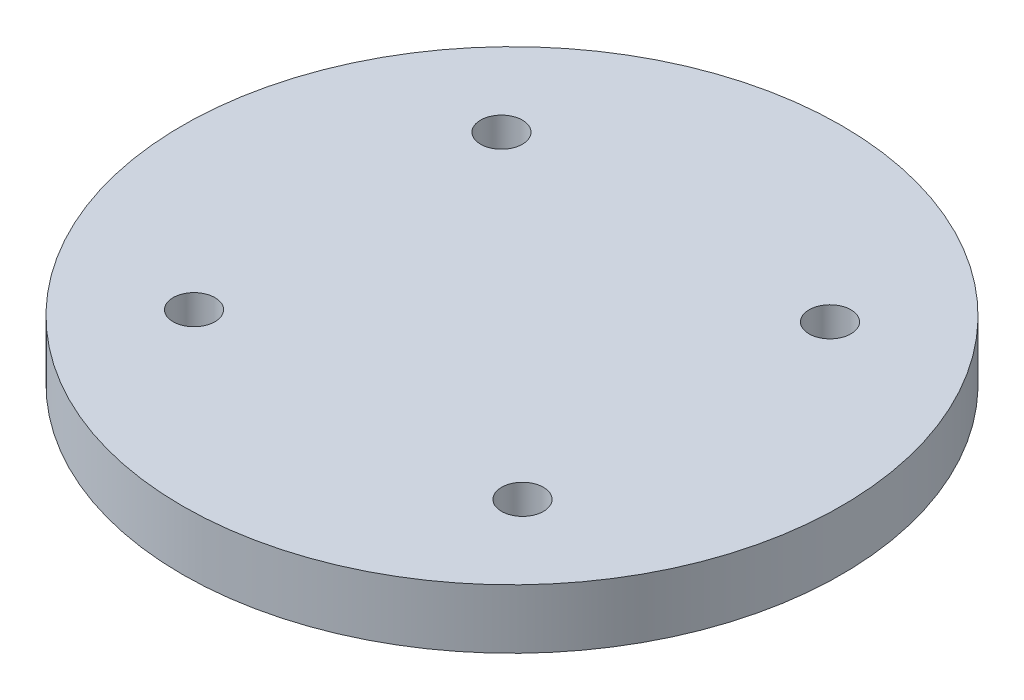
SolidWorks part; units mm, degrees
ref_plane "Front Plane" through (0, 0, 0) normal (0, 0, 1) x (1, 0, 0)
ref_plane "Top Plane" through (0, 0, 0) normal (0, 1, 0) x (1, 0, 0)
ref_plane "Right Plane" through (0, 0, 0) normal (1, 0, 0) x (0, 0, -1)
sketch "Sketch1" plane through (0, 0, 0) normal (0, 1, 0) x (1, 0, 0)
  line L0 (-59, 55.5) -> (-59, -55.5)
  line L1 (-50, 46.5) -> (50, 46.5)
  line L2 (-50, 46.5) -> (-50, -46.5)
  line L3 (-50, -46.5) -> (50, -46.5)
  line L4 (50, 46.5) -> (50, -46.5)
  line L5 (-50, 46.5) -> (50, -46.5) construction
  line L6 (-50, -46.5) -> (50, 46.5) construction
  line L7 (-59, -55.5) -> (59, -55.5)
  line L8 (59, 55.5) -> (59, -55.5)
  line L9 (-59, 55.5) -> (59, 55.5)
  circle A0 centre (0, 0) radius 81.0015
  circle A1 centre (0, 0) radius 50
  point P0 (0, 0)
  dimension "D4" = 100
  dimension "D1" = 100
  dimension "D2" = 93
  dimension "D3" = 9
extrude "Boss-Extrude1" add sketch "Sketch1" along normal blind 9 contours A1
sketch "Sketch2" plane through (0, 9, 0) normal (0, 1, 0) x (1, 0, 0)
  line L0 (0, 23.325) -> (0, -23.325) construction
  line L1 (-24.92, 23.325) -> (24.92, 23.325)
  line L2 (-24.92, 23.325) -> (-24.92, -23.325)
  line L3 (-24.92, -23.325) -> (24.92, -23.325)
  line L4 (24.92, 23.325) -> (24.92, -23.325)
  line L5 (-24.92, 23.325) -> (24.92, -23.325) construction
  line L6 (-24.92, -23.325) -> (24.92, 23.325) construction
  line L7 (-24.92, 0) -> (24.92, 0)
  line L8 (-24.92, 23.325) -> (24.92, 23.325)
  circle A0 centre (-24.92, -23.325) radius 3.175
  circle A1 centre (24.92, -23.325) radius 3.175
  circle A2 centre (24.92, 23.325) radius 3.175
  circle A3 centre (-24.92, 23.325) radius 3.175
  point P0 (0, 0)
  dimension "D3" = 6.35
  dimension "D1" = 46.65
  dimension "D2" = 49.84
extrude "Cut-Extrude1" cut sketch "Sketch2" against normal through all contours A0 | A1 | A2 | A3
